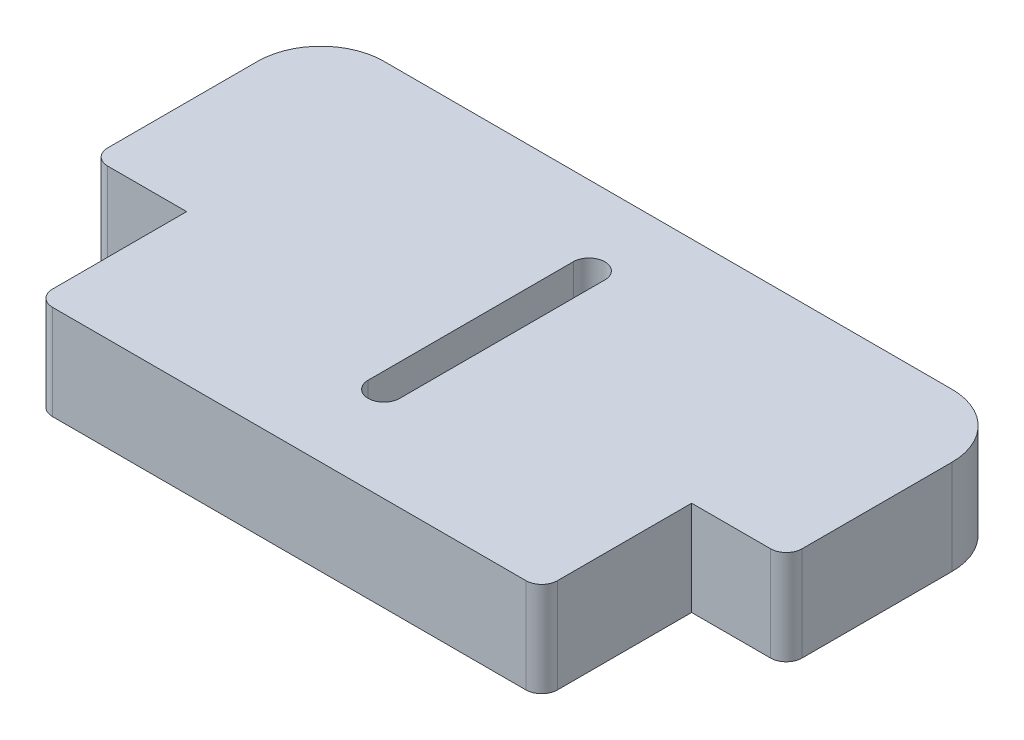
SolidWorks part; units mm, degrees
ref_plane "Front Plane" through (0, 0, 0) normal (0, 0, 1) x (1, 0, 0)
ref_plane "Top Plane" through (0, 0, 0) normal (0, 1, 0) x (1, 0, 0)
ref_plane "Right Plane" through (0, 0, 0) normal (1, 0, 0) x (0, 0, -1)
sketch "Sketch1" plane through (0, 0, 0) normal (0, 1, 0) x (1, 0, 0)
  line L0 (8.5553, 100.3817) -> (8.5553, 93.8817) construction
  line L1 (19.5553, 90.8817) -> (-2.4447, 90.8817)
  line L2 (19.5553, 90.8817) -> (19.5553, 102.8817)
  line L3 (19.5553, 102.8817) -> (-2.4447, 102.8817)
  line L4 (-2.4447, 90.8817) -> (-2.4447, 102.8817)
  line L5 (16.5553, 95.6317) -> (19.5553, 95.6317)
  line L6 (16.5553, 95.6317) -> (16.5553, 90.8817)
  line L7 (16.5553, 90.8817) -> (19.5553, 90.8817)
  line L8 (19.5553, 95.6317) -> (19.5553, 90.8817)
  line L9 (0.5553, 95.6317) -> (-2.4447, 95.6317)
  line L10 (0.5553, 95.6317) -> (0.5553, 90.8817)
  line L11 (0.5553, 90.8817) -> (-2.4447, 90.8817)
  line L12 (-2.4447, 95.6317) -> (-2.4447, 90.8817)
  line L13 (9.0553, 100.3817) -> (9.0553, 93.8817)
  line L14 (8.0553, 100.3817) -> (8.0553, 93.8817)
  arc A0 (9.0553, 100.3817) -> (8.0553, 100.3817) centre (8.5553, 100.3817) ccw
  arc A1 (8.0553, 93.8817) -> (9.0553, 93.8817) centre (8.5553, 93.8817) ccw
  point P9 (8.5553, 97.1317)
  point P17 (8.5553, 100.8817)
  dimension "D7" = 11
  dimension "D10" = 3
  dimension "D1" = 22
  dimension "D2" = 12
  dimension "D3" = 3
  dimension "D4" = 3
  dimension "D5" = 4.75
  dimension "D6" = 4.75
  dimension "D8" = 11
  dimension "D9" = 2
extrude "Boss-Extrude1" add sketch "Sketch1" along normal blind 3 contours L9 L10 L1 L6 L5 L2 L3 L4
fillet "Fillet1" radius 2 2 edges at (19.5553, 1.5, -102.8817) (-2.4447, 1.5, -102.8817)
fillet "Fillet2" radius 0.5 4 edges at (-2.4447, 1.5, -95.6317) (19.5553, 1.5, -95.6317) (16.5553, 1.5, -90.8817) (0.5553, 1.5, -90.8817)
